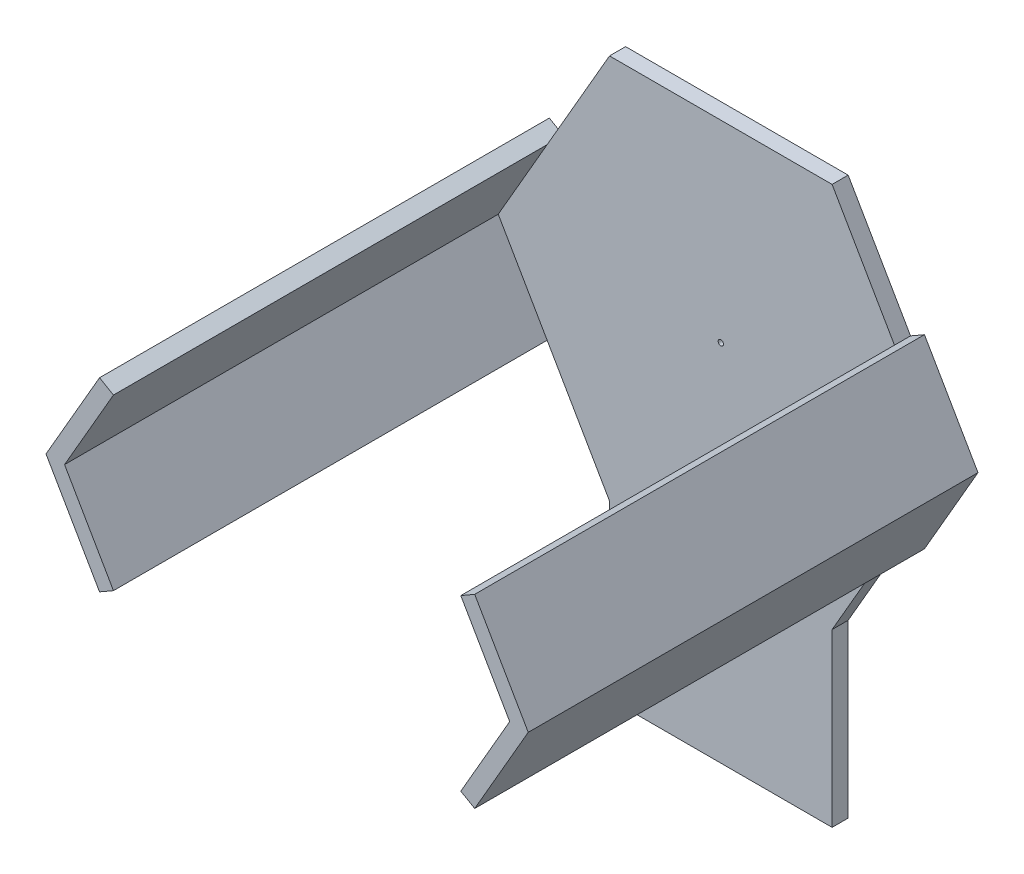
SolidWorks part; units mm, degrees
ref_plane "Front Plane" through (0, 0, 0) normal (0, 0, 1) x (1, 0, 0)
ref_plane "Top Plane" through (0, 0, 0) normal (0, 1, 0) x (1, 0, 0)
ref_plane "Right Plane" through (0, 0, 0) normal (1, 0, 0) x (0, 0, -1)
sketch "Sketch1" plane through (0, 0, 0) normal (0, 0, 1) x (1, 0, 0)
  line L0 (0, 0) -> (-131.9823, 228.6)
  line L1 (-131.9823, 228.6) -> (131.9823, 228.6)
  line L2 (131.9823, 228.6) -> (0, 0)
  line L3 (0, 0) -> (131.9823, 228.6)
  line L4 (131.9823, 228.6) -> (263.9645, 0)
  line L5 (263.9645, 0) -> (0, 0)
  line L6 (0, 0) -> (263.9645, 0)
  line L7 (263.9645, 0) -> (131.9823, -228.6)
  line L8 (131.9823, -228.6) -> (0, 0)
  line L9 (0, 0) -> (131.9823, -228.6)
  line L10 (131.9823, -228.6) -> (-131.9823, -228.6)
  line L11 (-131.9823, -228.6) -> (0, 0)
  line L12 (0, 0) -> (-131.9823, -228.6)
  line L13 (-131.9823, -228.6) -> (-263.9645, 0)
  line L14 (-263.9645, 0) -> (0, 0)
  line L15 (0, 0) -> (-263.9645, 0)
  line L16 (-263.9645, 0) -> (-131.9823, 228.6)
  line L17 (-131.9823, 228.6) -> (0, 0)
  point P29 (0, 0)
  dimension "D1" = 60
  dimension "D3" = 228.6
  dimension "D5" = 6
extrude "Boss-Extrude1" add sketch "Sketch1" along normal blind 19.05
sketch "Sketch2" plane through (0, 0, 19.05) normal (0, 0, 1) x (1, 0, 0)
  line L1 (-131.9823, -228.6) -> (131.9823, -228.6)
  line L2 (-131.9823, -228.6) -> (-131.9823, -431.8)
  line L3 (-131.9823, -431.8) -> (131.9823, -431.8)
  line L4 (131.9823, -228.6) -> (131.9823, -431.8)
  dimension "D1" = 0
  dimension "D2" = 203.2
extrude "Boss-Extrude2" add sketch "Sketch2" against normal blind 19.05
sketch "Sketch3" plane through (0, 0, 0) normal (0, 0, -1) x (-1, 0, 0)
  line L0 (205.9638, 100.4602) -> (269.4638, -9.525)
  line L1 (205.9638, 100.4602) -> (222.4616, 109.9852)
  line L2 (269.4638, -9.525) -> (285.9616, 0)
  line L3 (222.4616, 109.9852) -> (285.9616, 0)
  line L4 (263.9645, 0) -> (131.9823, 228.6) construction
  line L5 (205.9638, -100.4602) -> (269.4638, 9.525)
  line L6 (205.9638, -100.4602) -> (222.4616, -109.9852)
  line L7 (269.4638, 9.525) -> (285.9616, 0)
  line L8 (222.4616, -109.9852) -> (285.9616, 0)
  line L9 (131.9823, -228.6) -> (263.9645, 0) construction
  line L10 (0, 164.7532) -> (0, -180.3055) construction
  line L11 (-222.4616, -109.9852) -> (-285.9616, 0)
  line L12 (-269.4638, 9.525) -> (-285.9616, 0)
  line L13 (-205.9638, -100.4602) -> (-222.4616, -109.9852)
  line L14 (-205.9638, -100.4602) -> (-269.4638, 9.525)
  line L15 (-222.4616, 109.9852) -> (-285.9616, 0)
  line L16 (-269.4638, -9.525) -> (-285.9616, 0)
  line L17 (-205.9638, 100.4602) -> (-222.4616, 109.9852)
  line L18 (-205.9638, 100.4602) -> (-269.4638, -9.525)
  dimension "D1" = 120
  dimension "D2" = 19.05
  dimension "D3" = 19.05
  dimension "D4" = 127
  dimension "D5" = 127
extrude "Boss-Extrude3" add sketch "Sketch3" against normal blind 533.4 separate body contours L6 L8 L2 L0 L5 | L7 L5 L0 L2 | L5 L7 L3 L1 L0 | L14 L18 L16 L11 L13 | L18 L14 L12 L16 | L18 L17 L15 L12 L14
sketch "Sketch4" plane through (0, 0, 19.05) normal (0, 0, 1) x (1, 0, 0)
  circle A0 centre (0, 0) radius 3.175
  circle A1 centre (0, -320.802) radius 3.175
  dimension "D1" = 320.802
extrude "Cut-Extrude1" cut sketch "Sketch4" against normal through all
